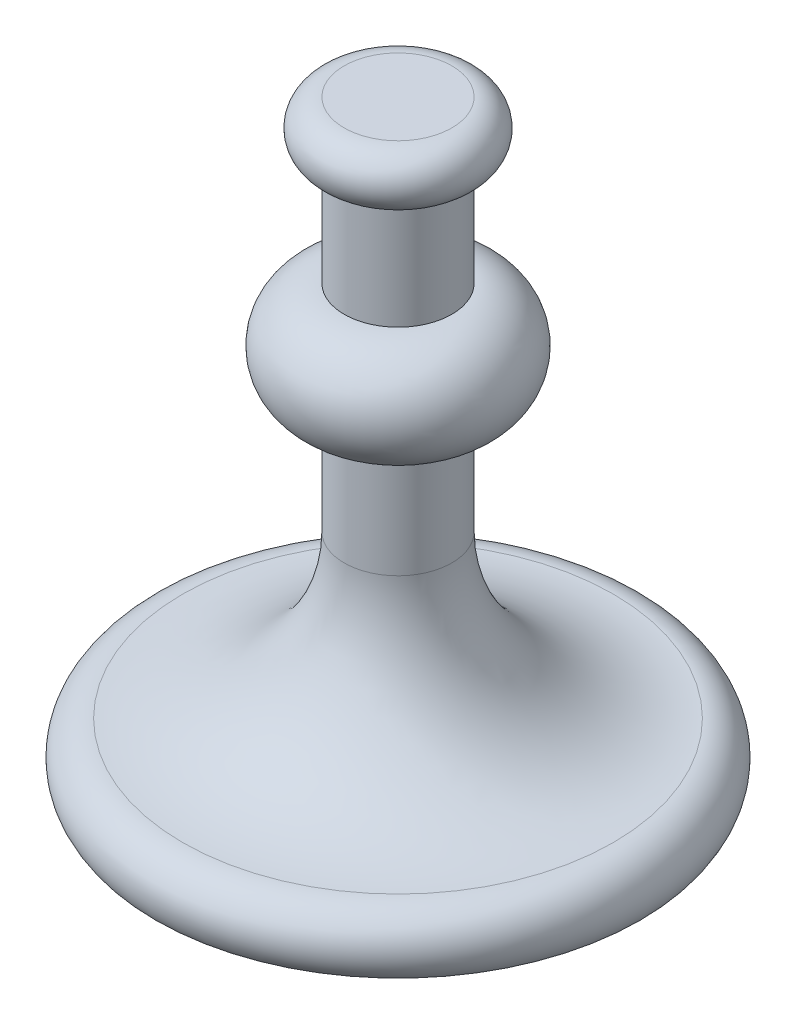
SolidWorks part; units mm, degrees
material "Pure Gold"
ref_plane "Front Plane" through (0, 0, 0) normal (0, 0, 1) x (1, 0, 0)
ref_plane "Top Plane" through (0, 0, 0) normal (0, 1, 0) x (1, 0, 0)
ref_plane "Right Plane" through (0, 0, 0) normal (1, 0, 0) x (0, 0, -1)
sketch "Sketch1" plane through (0, 0, 0) normal (0, 0, 1) x (1, 0, 0)
  line L0 (0, 0) -> (0, 220)
  line L1 (0, 220) -> (20, 220)
  line L2 (0, 0) -> (90, 0)
  line L3 (20, 200) -> (20, 160)
  line L4 (20, 120) -> (20, 80)
  arc A0 (20, 220) -> (20, 200) centre (20, 210) cw
  arc A1 (20, 160) -> (20, 120) centre (20, 140) cw
  arc A2 (20, 80) -> (80, 20) centre (80, 80) ccw
  arc A3 (80, 20) -> (90, 0) centre (80, 7.5) cw
  point P14 (0, 0)
  point P15 (0, 0)
  dimension "D4" = 10
  dimension "D6" = 20
  dimension "D7" = 60
  dimension "D9" = 12.5
  dimension "D1" = 20
  dimension "D2" = 220
  dimension "D3" = 90
  dimension "D5" = 40
  dimension "D8" = 80
revolve "Revolve1" add sketch "Sketch1" angle 360 about L0
